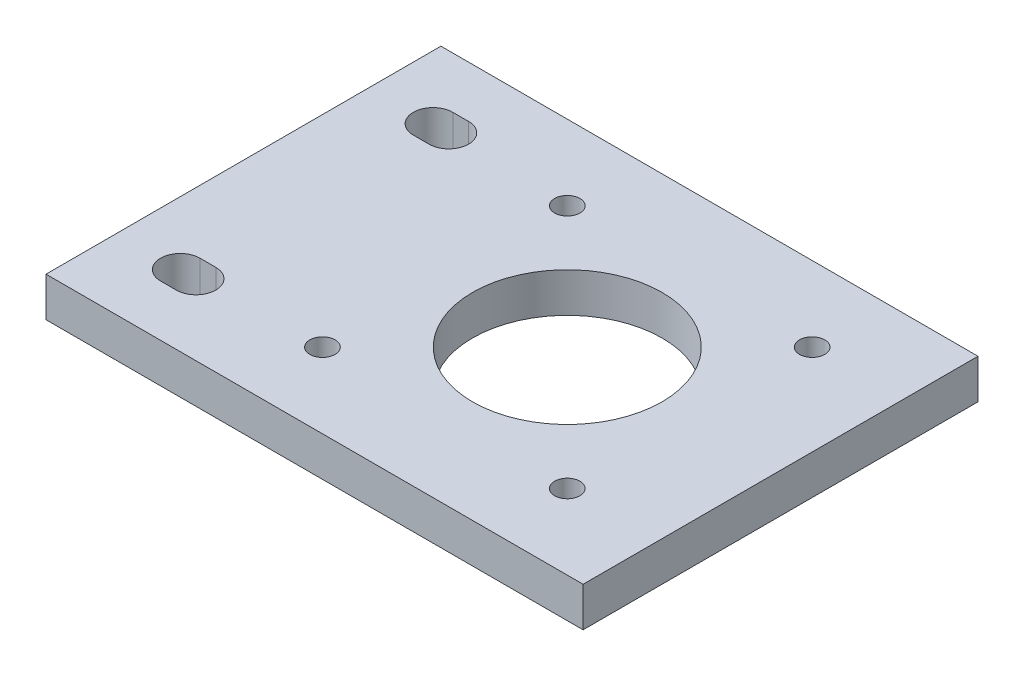
SolidWorks part; units mm, degrees
ref_plane "前视基准面" through (0, 0, 0) normal (0, 0, 1) x (1, 0, 0)
ref_plane "上视基准面" through (0, 0, 0) normal (0, 1, 0) x (1, 0, 0)
ref_plane "右视基准面" through (0, 0, 0) normal (1, 0, 0) x (0, 0, -1)
sketch "草图1" plane through (0, 0, 0) normal (0, 1, 0) x (1, 0, 0)
  line L0 (0, -25) -> (68, -25) construction
  line L1 (0, 0) -> (68, 0)
  line L2 (0, 0) -> (0, -50)
  line L3 (0, -50) -> (68, -50)
  line L4 (68, 0) -> (68, -50)
  line L5 (41, 0) -> (41, -50) construction
  line L6 (25.5, 0) -> (25.5, -50) construction
  line L7 (56.5, 0) -> (56.5, -50) construction
  line L8 (25.5, -9.5) -> (56.5, -9.5) construction
  line L9 (25.5, -40.5) -> (56.5, -40.5) construction
  line L10 (8, -6.5) -> (10, -6.5)
  line L11 (8, -11.5) -> (10, -11.5)
  line L12 (8, -38.5) -> (10, -38.5)
  line L13 (8, -43.5) -> (10, -43.5)
  arc A0 (8, -6.5) -> (8, -11.5) centre (8, -9) ccw
  arc A1 (8, -38.5) -> (8, -43.5) centre (8, -41) ccw
  circle A2 centre (41, -25) radius 12
  circle A3 centre (25.5, -9.5) radius 1.6
  circle A4 centre (56.5, -9.5) radius 1.6
  circle A5 centre (56.5, -40.5) radius 1.6
  circle A6 centre (25.5, -40.5) radius 1.6
  arc A7 (10, -11.5) -> (10, -6.5) centre (10, -9) ccw
  arc A8 (10, -43.5) -> (10, -38.5) centre (10, -41) ccw
  dimension "D3" = 5
  dimension "D4" = 5
  dimension "D7" = 16
  dimension "D8" = 16
  dimension "D10" = 24
  dimension "D15" = 3.2
  dimension "D16" = 5
  dimension "D17" = 2
  dimension "D18" = 5
  dimension "D19" = 10
  dimension "D1" = 68
  dimension "D2" = 50
  dimension "D5" = 8
  dimension "D6" = 8
  dimension "D9" = 27
  dimension "D11" = 15.5
  dimension "D12" = 15.5
  dimension "D13" = 15.5
  dimension "D14" = 15.5
  dimension "10" = 10
extrude "凸台-拉伸1" add sketch "草图1" along normal blind 5
